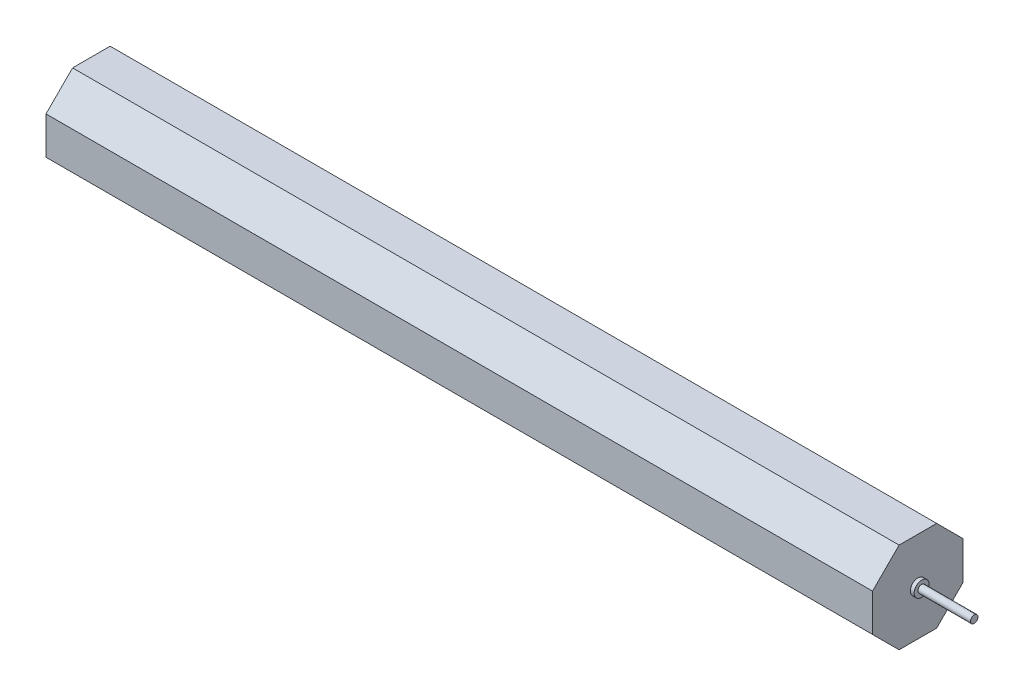
SolidWorks part; units mm, degrees
ref_plane "前视基准面" through (0, 0, 0) normal (0, 0, 1) x (1, 0, 0)
ref_plane "上视基准面" through (0, 0, 0) normal (0, 1, 0) x (1, 0, 0)
ref_plane "右视基准面" through (0, 0, 0) normal (1, 0, 0) x (0, 0, -1)
other "Configuration Table"
sketch "草图1" plane through (0, 0, 0) normal (1, 0, 0) x (0, 0, -1)
  line L1 (12.0711, -5) -> (12.0711, 5)
  line L2 (12.0711, 5) -> (5, 12.0711)
  line L3 (5, 12.0711) -> (-5, 12.0711)
  line L4 (-5, 12.0711) -> (-12.0711, 5)
  line L5 (-12.0711, 5) -> (-12.0711, -5)
  line L6 (-12.0711, -5) -> (-5, -12.0711)
  line L7 (-5, -12.0711) -> (5, -12.0711)
  line L8 (5, -12.0711) -> (12.0711, -5)
  circle A0 centre (0, 0) radius 12.0711 construction
  dimension "D1" = 10
extrude "凸台-拉伸1" add sketch "草图1" along normal blind 220
sketch "草图2" plane through (0, 12.0711, 0) normal (0, 1, 0) x (1, 0, 0)
  line L0 (9.4384, -2.3461) -> (9.352, -2.1662)
  line L1 (9.352, -2.1662) -> (9.8774, -1.7488)
  line L2 (9.8774, -1.7488) -> (9.9997, -1.8064)
  line L3 (11.1224, -1.9863) -> (11.4319, -2.0078)
  line L4 (11.4319, -2.0078) -> (11.6478, -2.0151)
  line L5 (11.6478, -2.0151) -> (11.655, -1.5833)
  line L6 (9.9134, -0.9068) -> (9.8702, -0.7341)
  line L7 (9.8702, -0.7341) -> (10.0933, -0.5901)
  line L8 (10.0933, -0.5901) -> (10.1005, -0.5829)
  line L9 (9.8126, 0.6981) -> (10.2732, 1.1299)
  line L10 (11.6406, 0.7557) -> (11.6765, 0.7629)
  line L11 (11.6765, 0.7629) -> (11.6622, 0.9284)
  line L12 (11.5902, 1.4249) -> (11.9284, 1.684)
  line L13 (11.9284, 1.684) -> (11.5686, 1.7272)
  line L14 (11.5686, 1.7272) -> (10.5467, 1.828)
  line L15 (9.6975, 1.828) -> (9.6399, 1.828)
  line L16 (9.6399, 1.828) -> (9.5247, 2.0151)
  line L17 (9.5247, 2.0151) -> (10.1365, 2.4037)
  line L18 (12.3746, 2.0367) -> (12.5186, 2.051)
  line L19 (12.5186, 2.051) -> (12.5617, 1.8711)
  line L20 (12.5617, 1.8711) -> (12.1515, 1.648)
  line L21 (12.0292, 1.1011) -> (11.9644, 0)
  line L22 (11.9788, -1.9647) -> (11.9788, -2.0294)
  line L23 (11.9788, -2.0294) -> (12.6265, -2.0294)
  line L24 (12.6265, -2.0294) -> (12.6625, -2.159)
  line L25 (12.6625, -2.159) -> (12.2451, -2.4541)
  line L26 (12.3386, -1.6264) -> (12.3962, -1.4897)
  line L27 (13.339, -1.7488) -> (13.3462, -1.3889)
  line L28 (13.3606, -0.6909) -> (12.5761, -0.5829)
  line L29 (12.5761, -0.5829) -> (12.5401, -0.4822)
  line L30 (12.5401, -0.4822) -> (12.8496, -0.2591)
  line L31 (13.2886, 0.3886) -> (13.5261, 0.6621)
  line L32 (12.792, 0.7197) -> (12.7489, 0.8564)
  line L33 (12.7489, 0.8564) -> (12.9216, 0.9715)
  line L34 (12.9216, 0.9715) -> (12.9288, 1.0579)
  line L35 (12.9288, 1.0579) -> (12.9, 1.4249)
  line L36 (12.7057, 2.0655) -> (13.0727, 2.4037)
  line L37 (13.0727, 2.4037) -> (13.1231, 2.3533)
  line L38 (13.4613, 2.1662) -> (13.6197, 2.1302)
  line L39 (14.0802, 2.0583) -> (14.4473, 2.3821)
  line L40 (14.4473, 2.3821) -> (14.548, 2.2741)
  line L41 (14.548, 2.2741) -> (14.5336, 2.2454)
  line L42 (14.3249, 0.5829) -> (14.109, 0.3742)
  line L43 (14.109, 0.3742) -> (14.0011, 0.403)
  line L44 (14.0011, 0.403) -> (14.0011, 0.5757)
  line L45 (14.0011, 0.5757) -> (13.7276, 0.6333)
  line L46 (13.7276, 0.6333) -> (13.6916, 0.5038)
  line L47 (13.6412, -1.7632) -> (13.6485, -1.8279)
  line L48 (13.6485, -1.8279) -> (14.145, -1.9215)
  line L49 (14.1306, -0.4174) -> (14.5984, -0.0648)
  line L50 (14.5984, -0.0648) -> (14.6632, -0.1799)
  line L51 (14.4473, -1.8208) -> (14.4688, -1.9791)
  line L52 (14.4688, -1.9791) -> (14.8935, -2.0223)
  line L53 (14.8935, -2.0223) -> (14.951, -2.1086)
  line L54 (14.951, -2.1086) -> (14.5336, -2.3605)
  line L55 (11.6765, -0.6837) -> (11.6765, 0.4534)
  line L56 (11.2303, 0.511) -> (10.777, 0.5613)
  line L57 (10.777, 0.5613) -> (10.3164, 0.5829)
  line L58 (11.3527, -0.6909) -> (11.6765, -0.6837)
  line L59 (8.6618, -2.4842) -> (8.6618, 2.5158) construction
  spline S0 degree 3 poles (12.2451, -2.4541) (11.9788, -2.3917) (11.4463, -2.2669) (10.5755, -2.2669) knots 0 0 0 0 1 1 1 1
  spline S1 degree 3 poles (10.5755, -2.2669) (10.3955, -2.2669) (10.0357, -2.2669) (9.4384, -2.3461) knots 1 1 1 1 2 2 2 2
  spline S2 degree 3 poles (9.9997, -1.8064) (10.0765, -1.8399) (10.23, -1.9071) (10.669, -1.9503) knots 5 5 5 5 6 6 6 6
  spline S3 degree 3 poles (10.669, -1.9503) (10.7698, -1.9599) (10.9713, -1.9791) (11.1224, -1.9863) knots 6 6 6 6 7 7 7 7
  spline S4 degree 3 poles (11.655, -1.5833) (11.6598, -1.4537) (11.6694, -1.1946) (11.6622, -1.0003) knots 10 10 10 10 11 11 11 11
  spline S5 degree 3 poles (11.6622, -1.0003) (11.4631, -0.962) (11.0648, -0.8852) (10.4315, -0.8852) knots 11 11 11 11 12 12 12 12
  spline S6 degree 3 poles (10.4315, -0.8852) (10.3452, -0.8852) (10.1725, -0.8852) (9.9134, -0.9068) knots 12 12 12 12 13 13 13 13
  spline S7 degree 3 poles (10.1005, -0.5829) (10.0981, -0.523) (10.0933, -0.403) (10.0789, -0.2123) knots 16 16 16 16 17 17 17 17
  spline S8 degree 3 poles (10.0789, -0.2123) (10.0741, -0.1487) (10.0645, -0.0216) (10.0285, 0.1295) knots 17 17 17 17 18 18 18 18
  spline S9 degree 3 poles (10.0285, 0.1295) (10.0165, 0.1967) (9.9925, 0.331) (9.9494, 0.4606) knots 18 18 18 18 19 19 19 19
  spline S10 degree 3 poles (9.9494, 0.4606) (9.9349, 0.5038) (9.9062, 0.5901) (9.8126, 0.6981) knots 19 19 19 19 20 20 20 20
  spline S11 degree 3 poles (10.2732, 1.1299) (10.3356, 1.0675) (10.4603, 0.9428) (10.7194, 0.878) knots 21 21 21 21 22 22 22 22
  spline S12 degree 3 poles (10.7194, 0.878) (10.8417, 0.8468) (11.0864, 0.7844) (11.6406, 0.7557) knots 22 22 22 22 23 23 23 23
  spline S13 degree 3 poles (11.6622, 0.9284) (11.6598, 0.9692) (11.655, 1.0507) (11.6406, 1.1839) knots 25 25 25 25 26 26 26 26
  spline S14 degree 3 poles (11.6406, 1.1839) (11.6358, 1.2283) (11.6262, 1.317) (11.5902, 1.4249) knots 26 26 26 26 27 27 27 27
  spline S15 degree 3 poles (10.5467, 1.828) (10.4747, 1.8351) (10.3308, 1.8495) (10.1221, 1.8495) knots 30 30 30 30 31 31 31 31
  spline S16 degree 3 poles (10.1221, 1.8495) (10.0477, 1.8495) (9.899, 1.8495) (9.6975, 1.828) knots 31 31 31 31 32 32 32 32
  spline S17 degree 3 poles (10.1365, 2.4037) (10.2036, 2.3365) (10.338, 2.2022) (10.6978, 2.1158) knots 35 35 35 35 36 36 36 36
  spline S18 degree 3 poles (10.6978, 2.1158) (10.7793, 2.0966) (10.9425, 2.0583) (11.2879, 2.0367) knots 36 36 36 36 37 37 37 37
  spline S19 degree 3 poles (11.2879, 2.0367) (11.3719, 2.0271) (11.5398, 2.0079) (11.8565, 2.0079) knots 37 37 37 37 38 38 38 38
  spline S20 degree 3 poles (11.8565, 2.0079) (11.9524, 2.0079) (12.1443, 2.0079) (12.3746, 2.0367) knots 38 38 38 38 39 39 39 39
  spline S21 degree 3 poles (12.1515, 1.648) (12.1179, 1.5641) (12.0508, 1.3962) (12.0292, 1.1011) knots 42 42 42 42 43 43 43 43
  spline S22 degree 3 poles (11.9644, 0) (11.962, -0.0911) (11.9572, -0.2735) (11.9572, -0.8132) knots 44 44 44 44 45 45 45 45
  spline S23 degree 3 poles (11.9572, -0.8132) (11.9572, -1.0051) (11.9572, -1.3889) (11.9788, -1.9647) knots 45 45 45 45 46 46 46 46
  spline S24 degree 3 poles (14.5336, -2.3605) (14.3705, -2.2981) (14.0442, -2.1734) (13.0511, -1.8567) knots 0 0 0 0 1 1 1 1
  spline S25 degree 3 poles (13.0511, -1.8567) (12.9719, -1.8327) (12.8136, -1.7848) (12.3386, -1.6264) knots 1 1 1 1 2 2 2 2
  spline S26 degree 3 poles (12.3962, -1.4897) (12.5665, -1.5401) (12.9072, -1.6409) (13.339, -1.7488) knots 3 3 3 3 4 4 4 4
  spline S27 degree 3 poles (13.3462, -1.3889) (13.3534, -1.257) (13.3678, -0.9931) (13.3606, -0.6909) knots 5 5 5 5 6 6 6 6
  spline S28 degree 3 poles (12.8496, -0.2591) (12.8832, -0.2927) (12.9504, -0.3598) (13.0727, -0.4066) knots 9 9 9 9 10 10 10 10
  spline S29 degree 3 poles (13.0727, -0.4066) (13.1135, -0.4222) (13.195, -0.4534) (13.3678, -0.475) knots 10 10 10 10 11 11 11 11
  spline S30 degree 3 poles (13.3678, -0.475) (13.3678, -0.3022) (13.3678, 0.0432) (13.2886, 0.3886) knots 11 11 11 11 12 12 12 12
  spline S31 degree 3 poles (13.5261, 0.6621) (13.3918, 0.6813) (13.1231, 0.7197) (12.792, 0.7197) knots 13 13 13 13 14 14 14 14
  spline S32 degree 3 poles (12.9, 1.4249) (12.8928, 1.4945) (12.8784, 1.6336) (12.8388, 1.7848) knots 18 18 18 18 19 19 19 19
  spline S33 degree 3 poles (12.8388, 1.7848) (12.8256, 1.8351) (12.7993, 1.9359) (12.7057, 2.0655) knots 19 19 19 19 20 20 20 20
  spline S34 degree 3 poles (13.1231, 2.3533) (13.1711, 2.3101) (13.267, 2.2238) (13.4613, 2.1662) knots 22 22 22 22 23 23 23 23
  spline S35 degree 3 poles (13.6197, 2.1302) (13.6916, 2.1134) (13.8355, 2.0798) (14.0802, 2.0583) knots 24 24 24 24 25 25 25 25
  spline S36 degree 3 poles (14.5336, 2.2454) (14.5049, 2.1926) (14.4473, 2.087) (14.4113, 1.9143) knots 28 28 28 28 29 29 29 29
  spline S37 degree 3 poles (14.4113, 1.9143) (14.3969, 1.8472) (14.3681, 1.7128) (14.3465, 1.4897) knots 29 29 29 29 30 30 30 30
  spline S38 degree 3 poles (14.3465, 1.4897) (14.3321, 1.3602) (14.3033, 1.1011) (14.3033, 0.9068) knots 30 30 30 30 31 31 31 31
  spline S39 degree 3 poles (14.3033, 0.9068) (14.3033, 0.854) (14.3033, 0.7484) (14.3249, 0.5829) knots 31 31 31 31 32 32 32 32
  spline S40 degree 3 poles (13.6916, 0.5038) (13.6652, 0.4126) (13.6125, 0.2303) (13.6125, -0.1727) knots 37 37 37 37 38 38 38 38
  spline S41 degree 3 poles (13.6125, -0.1727) (13.6101, -0.2207) (13.6053, -0.3167) (13.6053, -0.5973) knots 38 38 38 38 39 39 39 39
  spline S42 degree 3 poles (13.6053, -0.5973) (13.6053, -0.77) (13.6053, -1.1155) (13.6412, -1.7632) knots 39 39 39 39 40 40 40 40
  spline S43 degree 3 poles (14.145, -1.9215) (14.1546, -1.8663) (14.1738, -1.756) (14.1882, -1.4321) knots 42 42 42 42 43 43 43 43
  spline S44 degree 3 poles (14.1882, -1.4321) (14.193, -1.3458) (14.2026, -1.1731) (14.2026, -1.0507) knots 43 43 43 43 44 44 44 44
  spline S45 degree 3 poles (14.2026, -1.0507) (14.2026, -0.938) (14.2026, -0.7125) (14.1306, -0.4174) knots 44 44 44 44 45 45 45 45
  spline S46 degree 3 poles (14.6632, -0.1799) (14.6296, -0.2303) (14.5624, -0.331) (14.5192, -0.439) knots 47 47 47 47 48 48 48 48
  spline S47 degree 3 poles (14.5192, -0.439) (14.5049, -0.475) (14.4761, -0.5469) (14.4617, -0.7125) knots 48 48 48 48 49 49 49 49
  spline S48 degree 3 poles (14.4617, -0.7125) (14.4521, -0.8084) (14.4329, -1.0003) (14.4329, -1.353) knots 49 49 49 49 50 50 50 50
  spline S49 degree 3 poles (14.4329, -1.353) (14.4329, -1.4561) (14.4329, -1.6624) (14.4473, -1.8208) knots 50 50 50 50 51 51 51 51
  spline S50 degree 3 poles (14.0227, 0.8132) (14.0467, 1.0051) (14.0946, 1.3889) (14.0874, 1.8136) knots 4 4 4 4 5 5 5 5
  spline S51 degree 3 poles (13.2382, 0.9715) (13.3414, 0.9404) (13.5477, 0.878) (14.0227, 0.8132) knots 3 3 3 3 4 4 4 4
  spline S52 degree 3 poles (13.1591, 1.9503) (13.1663, 1.7608) (13.1807, 1.3818) (13.2382, 0.9715) knots 2 2 2 2 3 3 3 3
  spline S53 degree 3 poles (13.6448, 1.8999) (13.5141, 1.9191) (13.2526, 1.9575) (13.1591, 1.9503) knots 1 1 1 1 2 2 2 2
  spline S54 degree 3 poles (14.0874, 1.8136) (14.0706, 1.8231) (14.0371, 1.8424) (13.6448, 1.8999) knots 0 0 0 0 1 1 1 1
  spline S55 degree 3 poles (11.6765, 0.4534) (11.6286, 0.463) (11.5326, 0.4822) (11.2303, 0.511) knots 1 1 1 1 2 2 2 2
  spline S56 degree 3 poles (10.3164, 0.5829) (10.3164, 0.355) (10.3164, -0.1007) (10.4171, -0.5326) knots 4 4 4 4 5 5 5 5
  spline S57 degree 3 poles (10.4171, -0.5326) (10.4555, -0.5494) (10.5323, -0.5829) (10.669, -0.6189) knots 5 5 5 5 6 6 6 6
  spline S58 degree 3 poles (10.669, -0.6189) (10.7194, -0.6309) (10.8201, -0.6549) (11.0001, -0.6693) knots 6 6 6 6 7 7 7 7
  spline S59 degree 3 poles (11.0001, -0.6693) (11.06, -0.6741) (11.18, -0.6837) (11.3527, -0.6909) knots 7 7 7 7 8 8 8 8
  dimension "D1" = 5
sketch "草图3" plane through (0, 12.0711, 0) normal (0, 1, 0) x (1, 0, 0)
  line L0 (16.0742, -2.3589) -> (15.9878, -2.179)
  line L1 (15.9878, -2.179) -> (16.5131, -1.7616)
  line L2 (16.5131, -1.7616) -> (16.6355, -1.8191)
  line L3 (17.7582, -1.999) -> (18.0677, -2.0206)
  line L4 (18.0677, -2.0206) -> (18.2836, -2.0278)
  line L5 (18.2836, -2.0278) -> (18.2908, -1.596)
  line L6 (16.5492, -0.9195) -> (16.506, -0.7468)
  line L7 (16.506, -0.7468) -> (16.7291, -0.6029)
  line L8 (16.7291, -0.6029) -> (16.7363, -0.5957)
  line L9 (16.4484, 0.6853) -> (16.909, 1.1171)
  line L10 (18.2763, 0.7429) -> (18.3123, 0.7501)
  line L11 (18.3123, 0.7501) -> (18.2979, 0.9156)
  line L12 (18.226, 1.4122) -> (18.5642, 1.6713)
  line L13 (18.5642, 1.6713) -> (18.2044, 1.7144)
  line L14 (18.2044, 1.7144) -> (17.1825, 1.8152)
  line L15 (16.3332, 1.8152) -> (16.2757, 1.8152)
  line L16 (16.2757, 1.8152) -> (16.1605, 2.0023)
  line L17 (16.1605, 2.0023) -> (16.7723, 2.3909)
  line L18 (19.0104, 2.0239) -> (19.1544, 2.0383)
  line L19 (19.1544, 2.0383) -> (19.1975, 1.8584)
  line L20 (19.1975, 1.8584) -> (18.7873, 1.6353)
  line L21 (18.665, 1.0883) -> (18.6002, -0.0128)
  line L22 (18.6146, -1.9774) -> (18.6146, -2.0422)
  line L23 (18.6146, -2.0422) -> (19.2623, -2.0422)
  line L24 (19.2623, -2.0422) -> (19.2983, -2.1717)
  line L25 (19.2983, -2.1717) -> (18.8809, -2.4668)
  line L26 (18.9744, -1.6392) -> (19.032, -1.5025)
  line L27 (19.9748, -1.7616) -> (19.9819, -1.4017)
  line L28 (19.9964, -0.7036) -> (19.2119, -0.5957)
  line L29 (19.2119, -0.5957) -> (19.1759, -0.4949)
  line L30 (19.1759, -0.4949) -> (19.4854, -0.2718)
  line L31 (19.9244, 0.3759) -> (20.1619, 0.6493)
  line L32 (19.4278, 0.7069) -> (19.3847, 0.8436)
  line L33 (19.3847, 0.8436) -> (19.5574, 0.9588)
  line L34 (19.5574, 0.9588) -> (19.5646, 1.0451)
  line L35 (19.5646, 1.0451) -> (19.5358, 1.4122)
  line L36 (19.3415, 2.0527) -> (19.7085, 2.3909)
  line L37 (19.7085, 2.3909) -> (19.7589, 2.3406)
  line L38 (20.0971, 2.1534) -> (20.2554, 2.1175)
  line L39 (20.716, 2.0455) -> (21.0831, 2.3693)
  line L40 (21.0831, 2.3693) -> (21.1838, 2.2614)
  line L41 (21.1838, 2.2614) -> (21.1694, 2.2326)
  line L42 (20.9607, 0.5702) -> (20.7448, 0.3615)
  line L43 (20.7448, 0.3615) -> (20.6369, 0.3903)
  line L44 (20.6369, 0.3903) -> (20.6369, 0.563)
  line L45 (20.6369, 0.563) -> (20.3634, 0.6206)
  line L46 (20.3634, 0.6206) -> (20.3274, 0.491)
  line L47 (20.277, -1.7759) -> (20.2842, -1.8407)
  line L48 (20.2842, -1.8407) -> (20.7808, -1.9343)
  line L49 (20.7664, -0.4302) -> (21.2342, -0.0775)
  line L50 (21.2342, -0.0775) -> (21.299, -0.1927)
  line L51 (21.0831, -1.8335) -> (21.1046, -1.9918)
  line L52 (21.1046, -1.9918) -> (21.5292, -2.035)
  line L53 (21.5292, -2.035) -> (21.5868, -2.1214)
  line L54 (21.5868, -2.1214) -> (21.1694, -2.3732)
  line L55 (18.3123, -0.6964) -> (18.3123, 0.4406)
  line L56 (17.8661, 0.4982) -> (17.4127, 0.5486)
  line L57 (17.4127, 0.5486) -> (16.9522, 0.5702)
  line L58 (17.9885, -0.7036) -> (18.3123, -0.6964)
  spline S0 degree 3 poles (18.8809, -2.4668) (18.6146, -2.4044) (18.082, -2.2797) (17.2112, -2.2797) knots 0 0 0 0 1 1 1 1
  spline S1 degree 3 poles (17.2112, -2.2797) (17.0313, -2.2797) (16.6715, -2.2797) (16.0742, -2.3589) knots 1 1 1 1 2 2 2 2
  spline S2 degree 3 poles (16.6355, -1.8191) (16.7123, -1.8527) (16.8658, -1.9199) (17.3048, -1.9631) knots 5 5 5 5 6 6 6 6
  spline S3 degree 3 poles (17.3048, -1.9631) (17.4056, -1.9726) (17.6071, -1.9918) (17.7582, -1.999) knots 6 6 6 6 7 7 7 7
  spline S4 degree 3 poles (18.2908, -1.596) (18.2955, -1.4665) (18.3051, -1.2074) (18.2979, -1.0131) knots 10 10 10 10 11 11 11 11
  spline S5 degree 3 poles (18.2979, -1.0131) (18.0988, -0.9747) (17.7006, -0.898) (17.0673, -0.898) knots 11 11 11 11 12 12 12 12
  spline S6 degree 3 poles (17.0673, -0.898) (16.9809, -0.898) (16.8082, -0.898) (16.5492, -0.9195) knots 12 12 12 12 13 13 13 13
  spline S7 degree 3 poles (16.7363, -0.5957) (16.7339, -0.5357) (16.7291, -0.4158) (16.7147, -0.2251) knots 16 16 16 16 17 17 17 17
  spline S8 degree 3 poles (16.7147, -0.2251) (16.7099, -0.1615) (16.7003, -0.0344) (16.6643, 0.1168) knots 17 17 17 17 18 18 18 18
  spline S9 degree 3 poles (16.6643, 0.1168) (16.6523, 0.184) (16.6283, 0.3183) (16.5851, 0.4478) knots 18 18 18 18 19 19 19 19
  spline S10 degree 3 poles (16.5851, 0.4478) (16.5707, 0.491) (16.542, 0.5774) (16.4484, 0.6853) knots 19 19 19 19 20 20 20 20
  spline S11 degree 3 poles (16.909, 1.1171) (16.9713, 1.0548) (17.0961, 0.93) (17.3552, 0.8652) knots 21 21 21 21 22 22 22 22
  spline S12 degree 3 poles (17.3552, 0.8652) (17.4775, 0.834) (17.7222, 0.7717) (18.2763, 0.7429) knots 22 22 22 22 23 23 23 23
  spline S13 degree 3 poles (18.2979, 0.9156) (18.2955, 0.9564) (18.2908, 1.038) (18.2763, 1.1711) knots 25 25 25 25 26 26 26 26
  spline S14 degree 3 poles (18.2763, 1.1711) (18.2716, 1.2155) (18.2619, 1.3042) (18.226, 1.4122) knots 26 26 26 26 27 27 27 27
  spline S15 degree 3 poles (17.1825, 1.8152) (17.1105, 1.8224) (16.9665, 1.8368) (16.7578, 1.8368) knots 30 30 30 30 31 31 31 31
  spline S16 degree 3 poles (16.7578, 1.8368) (16.6835, 1.8368) (16.5348, 1.8368) (16.3332, 1.8152) knots 31 31 31 31 32 32 32 32
  spline S17 degree 3 poles (16.7723, 2.3909) (16.8394, 2.3238) (16.9737, 2.1894) (17.3336, 2.1031) knots 35 35 35 35 36 36 36 36
  spline S18 degree 3 poles (17.3336, 2.1031) (17.4151, 2.0839) (17.5783, 2.0455) (17.9237, 2.0239) knots 36 36 36 36 37 37 37 37
  spline S19 degree 3 poles (17.9237, 2.0239) (18.0077, 2.0143) (18.1756, 1.9951) (18.4923, 1.9951) knots 37 37 37 37 38 38 38 38
  spline S20 degree 3 poles (18.4923, 1.9951) (18.5882, 1.9951) (18.7801, 1.9951) (19.0104, 2.0239) knots 38 38 38 38 39 39 39 39
  spline S21 degree 3 poles (18.7873, 1.6353) (18.7537, 1.5513) (18.6866, 1.3834) (18.665, 1.0883) knots 42 42 42 42 43 43 43 43
  spline S22 degree 3 poles (18.6002, -0.0128) (18.5978, -0.1039) (18.593, -0.2862) (18.593, -0.826) knots 44 44 44 44 45 45 45 45
  spline S23 degree 3 poles (18.593, -0.826) (18.593, -1.0179) (18.593, -1.4017) (18.6146, -1.9774) knots 45 45 45 45 46 46 46 46
  spline S24 degree 3 poles (21.1694, -2.3732) (21.0063, -2.3109) (20.68, -2.1862) (19.6869, -1.8695) knots 0 0 0 0 1 1 1 1
  spline S25 degree 3 poles (19.6869, -1.8695) (19.6077, -1.8455) (19.4494, -1.7975) (18.9744, -1.6392) knots 1 1 1 1 2 2 2 2
  spline S26 degree 3 poles (19.032, -1.5025) (19.2023, -1.5528) (19.543, -1.6536) (19.9748, -1.7616) knots 3 3 3 3 4 4 4 4
  spline S27 degree 3 poles (19.9819, -1.4017) (19.9892, -1.2698) (20.0036, -1.0059) (19.9964, -0.7036) knots 5 5 5 5 6 6 6 6
  spline S28 degree 3 poles (19.4854, -0.2718) (19.519, -0.3054) (19.5861, -0.3726) (19.7085, -0.4194) knots 9 9 9 9 10 10 10 10
  spline S29 degree 3 poles (19.7085, -0.4194) (19.7492, -0.4349) (19.8308, -0.4661) (20.0036, -0.4877) knots 10 10 10 10 11 11 11 11
  spline S30 degree 3 poles (20.0036, -0.4877) (20.0036, -0.315) (20.0036, 0.0304) (19.9244, 0.3759) knots 11 11 11 11 12 12 12 12
  spline S31 degree 3 poles (20.1619, 0.6493) (20.0275, 0.6685) (19.7589, 0.7069) (19.4278, 0.7069) knots 13 13 13 13 14 14 14 14
  spline S32 degree 3 poles (19.5358, 1.4122) (19.5286, 1.4818) (19.5142, 1.6209) (19.4746, 1.772) knots 18 18 18 18 19 19 19 19
  spline S33 degree 3 poles (19.4746, 1.772) (19.4614, 1.8224) (19.435, 1.9232) (19.3415, 2.0527) knots 19 19 19 19 20 20 20 20
  spline S34 degree 3 poles (19.7589, 2.3406) (19.8068, 2.2974) (19.9028, 2.211) (20.0971, 2.1534) knots 22 22 22 22 23 23 23 23
  spline S35 degree 3 poles (20.2554, 2.1175) (20.3274, 2.1007) (20.4713, 2.0671) (20.716, 2.0455) knots 24 24 24 24 25 25 25 25
  spline S36 degree 3 poles (21.1694, 2.2326) (21.1406, 2.1798) (21.0831, 2.0743) (21.0471, 1.9016) knots 28 28 28 28 29 29 29 29
  spline S37 degree 3 poles (21.0471, 1.9016) (21.0327, 1.8344) (21.0039, 1.7001) (20.9823, 1.477) knots 29 29 29 29 30 30 30 30
  spline S38 degree 3 poles (20.9823, 1.477) (20.9679, 1.3474) (20.9391, 1.0883) (20.9391, 0.894) knots 30 30 30 30 31 31 31 31
  spline S39 degree 3 poles (20.9391, 0.894) (20.9391, 0.8413) (20.9391, 0.7357) (20.9607, 0.5702) knots 31 31 31 31 32 32 32 32
  spline S40 degree 3 poles (20.3274, 0.491) (20.301, 0.3998) (20.2482, 0.2176) (20.2482, -0.1855) knots 37 37 37 37 38 38 38 38
  spline S41 degree 3 poles (20.2482, -0.1855) (20.2458, -0.2334) (20.2411, -0.3294) (20.2411, -0.6101) knots 38 38 38 38 39 39 39 39
  spline S42 degree 3 poles (20.2411, -0.6101) (20.2411, -0.7828) (20.2411, -1.1282) (20.277, -1.7759) knots 39 39 39 39 40 40 40 40
  spline S43 degree 3 poles (20.7808, -1.9343) (20.7904, -1.8791) (20.8096, -1.7687) (20.8239, -1.4449) knots 42 42 42 42 43 43 43 43
  spline S44 degree 3 poles (20.8239, -1.4449) (20.8288, -1.3585) (20.8384, -1.1858) (20.8384, -1.0635) knots 43 43 43 43 44 44 44 44
  spline S45 degree 3 poles (20.8384, -1.0635) (20.8384, -0.9507) (20.8384, -0.7252) (20.7664, -0.4302) knots 44 44 44 44 45 45 45 45
  spline S46 degree 3 poles (21.299, -0.1927) (21.2654, -0.243) (21.1982, -0.3438) (21.155, -0.4517) knots 47 47 47 47 48 48 48 48
  spline S47 degree 3 poles (21.155, -0.4517) (21.1406, -0.4877) (21.1118, -0.5597) (21.0975, -0.7252) knots 48 48 48 48 49 49 49 49
  spline S48 degree 3 poles (21.0975, -0.7252) (21.0878, -0.8212) (21.0686, -1.0131) (21.0686, -1.3657) knots 49 49 49 49 50 50 50 50
  spline S49 degree 3 poles (21.0686, -1.3657) (21.0686, -1.4689) (21.0686, -1.6752) (21.0831, -1.8335) knots 50 50 50 50 51 51 51 51
  spline S50 degree 3 poles (20.6584, 0.8005) (20.6825, 0.9924) (20.7304, 1.3762) (20.7232, 1.8008) knots 4 4 4 4 5 5 5 5
  spline S51 degree 3 poles (19.874, 0.9588) (19.9772, 0.9276) (20.1835, 0.8652) (20.6584, 0.8005) knots 3 3 3 3 4 4 4 4
  spline S52 degree 3 poles (19.7948, 1.9376) (19.802, 1.748) (19.8164, 1.369) (19.874, 0.9588) knots 2 2 2 2 3 3 3 3
  spline S53 degree 3 poles (20.2806, 1.8872) (20.1499, 1.9064) (19.8884, 1.9447) (19.7948, 1.9376) knots 1 1 1 1 2 2 2 2
  spline S54 degree 3 poles (20.7232, 1.8008) (20.7064, 1.8104) (20.6728, 1.8296) (20.2806, 1.8872) knots 0 0 0 0 1 1 1 1
  spline S55 degree 3 poles (18.3123, 0.4406) (18.2643, 0.4503) (18.1684, 0.4694) (17.8661, 0.4982) knots 1 1 1 1 2 2 2 2
  spline S56 degree 3 poles (16.9522, 0.5702) (16.9522, 0.3423) (16.9522, -0.1135) (17.0529, -0.5453) knots 4 4 4 4 5 5 5 5
  spline S57 degree 3 poles (17.0529, -0.5453) (17.0913, -0.5621) (17.1681, -0.5957) (17.3048, -0.6317) knots 5 5 5 5 6 6 6 6
  spline S58 degree 3 poles (17.3048, -0.6317) (17.3552, -0.6437) (17.4559, -0.6676) (17.6359, -0.682) knots 6 6 6 6 7 7 7 7
  spline S59 degree 3 poles (17.6359, -0.682) (17.6958, -0.6868) (17.8158, -0.6964) (17.9885, -0.7036) knots 7 7 7 7 8 8 8 8
sketch "草图4" plane through (220, 0, 0) normal (1, 0, 0) x (0, 0, -1)
  circle A0 centre (0, 0) radius 1
  dimension "D1" = 2
extrude "凸台-拉伸2" add sketch "草图4" along normal blind 15
sketch "草图5" plane through (220, 0, 0) normal (1, 0, 0) x (0, 0, -1)
  circle A0 centre (0, 0) radius 2
  dimension "D1" = 4
extrude "凸台-拉伸3" add sketch "草图5" along normal blind 1 contours A0
sketch "草图6" plane through (0, 0, 0) normal (-1, 0, 0) x (0, 0, 1)
  circle A0 centre (0, 0) radius 1 construction
  circle A1 centre (0, 0) radius 1
extrude "凸台-拉伸4" add sketch "草图6" along normal blind 5
sketch "草图7" plane through (0, 0, 0) normal (-1, 0, 0) x (0, 0, 1)
  circle A0 centre (0, 0) radius 2 construction
  circle A1 centre (0, 0) radius 2
extrude "凸台-拉伸5" add sketch "草图7" along normal blind 1
